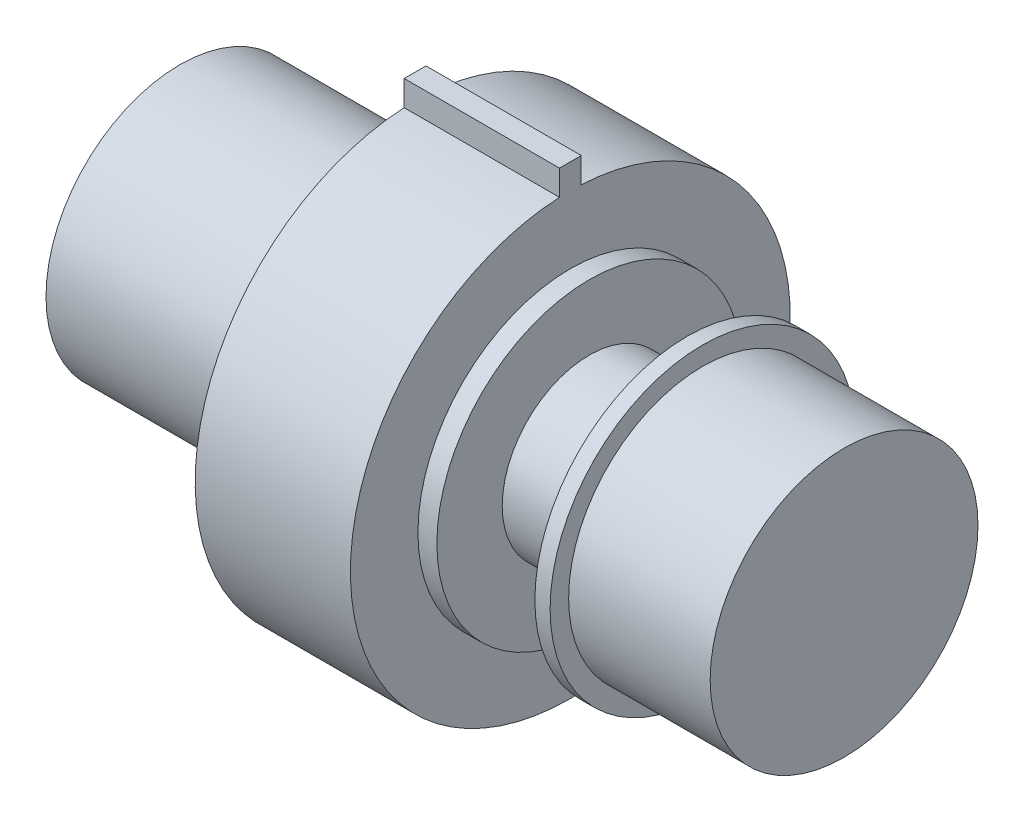
SolidWorks part; units mm, degrees
material "Acciaio al carbonio semplice"
ref_plane "Piano frontale" through (0, 0, 0) normal (0, 0, 1) x (1, 0, 0)
ref_plane "Piano superiore" through (0, 0, 0) normal (0, 1, 0) x (1, 0, 0)
ref_plane "Piano destro" through (0, 0, 0) normal (1, 0, 0) x (0, 0, -1)
sketch "Schizzo1" plane through (0, 0, 0) normal (0, 0, 1) x (1, 0, 0)
  line L0 (-1716.3243, 0) -> (84099.8918, 0) construction
  line L1 (-152.5, 0) -> (152.5, 0)
  line L2 (-152.5, 0) -> (-152.5, 61.5)
  line L3 (-152.5, 61.5) -> (-44.5, 61.5)
  line L4 (152.5, 0) -> (152.5, 61.5)
  line L5 (152.5, 61.5) -> (87.5, 61.5)
  line L6 (-44.5, 61.5) -> (-44.5, 101)
  line L7 (-44.5, 101) -> (26.8, 101)
  line L10 (26.8, 70) -> (35.5, 70)
  line L11 (35.5, 70) -> (35.5, 40)
  line L15 (80.5, 40) -> (80.5, 70)
  line L16 (80.5, 70) -> (87.5, 70)
  line L17 (87.5, 70) -> (87.5, 61.5)
  line L19 (35.5, 40) -> (80.5, 40)
  line L20 (26.8, 101) -> (26.8, 70)
  point P6 (0, 0)
  dimension "D1" = 305
  dimension "D2" = 61.5
  dimension "D3" = 108
  dimension "D5" = 39.5
  dimension "D6" = 7
  dimension "D7" = 30
  dimension "D8" = 8.7
  dimension "D9" = 45
  dimension "D10" = 65
  dimension "D11" = 40
revolve "Rivoluzione1" add sketch "Schizzo1" angle 360 about L0
sketch "Schizzo2" plane through (-44.5, 0, 0) normal (-1, 0, 0) x (0, 0, 1)
  line L0 (0, -1000) -> (0, 1018.1753) construction
  line L2 (-5, 77.5) -> (5, 77.5)
  line L3 (-5, 77.5) -> (-5, 112.5)
  line L4 (-5, 112.5) -> (5, 112.5)
  line L5 (5, 77.5) -> (5, 112.5)
  line L6 (-5, 77.5) -> (5, 112.5) construction
  line L7 (-5, 112.5) -> (5, 77.5) construction
  circle A0 centre (0, 0) radius 101 construction
  circle A1 centre (0, 0) radius 101 construction
  point P1 (0, 95)
  dimension "D1" = 10
  dimension "D2" = 95
  dimension "D3" = 35
extrude "Estrusione-Estrusione1" add sketch "Schizzo2" against normal up to surface (71.3 mm away) up to face at (26.8, 0, 101)
sketch "Schizzo3" plane through (0, 0, 0) normal (0, 0, 1) x (1, 0, 0)
  line L0 (152.5, 0) -> (-152.5, 0) construction
  line L1 (-152.5, 61.5) -> (-152.5, -61.5) construction
  point P6 (0, 0)
